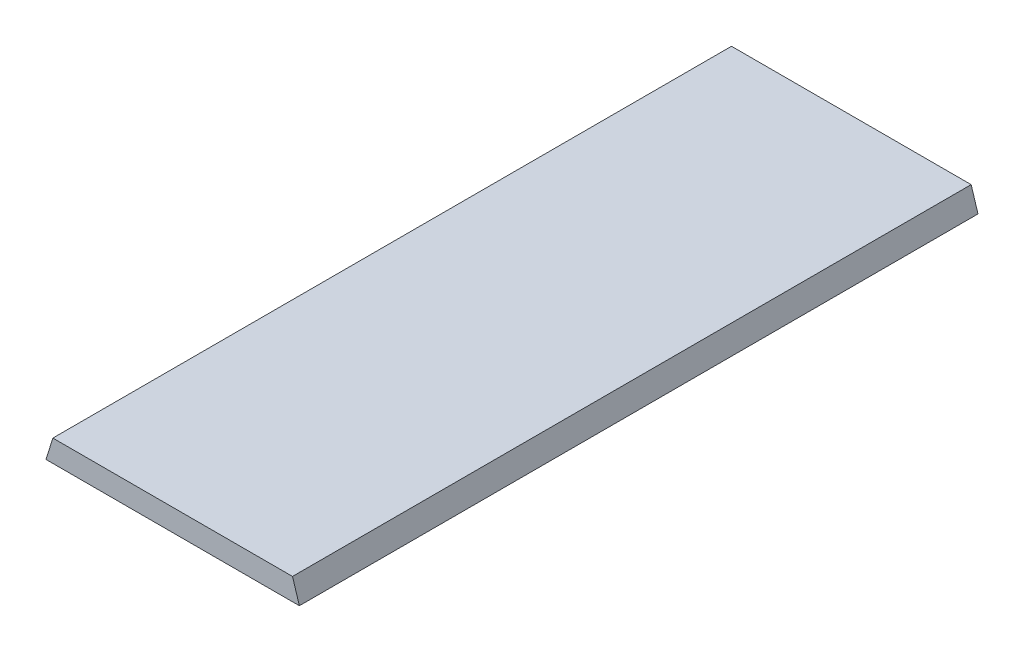
SolidWorks part; units mm, degrees
ref_plane "Front Plane" through (0, 0, 0) normal (0, 0, 1) x (1, 0, 0)
ref_plane "Top Plane" through (0, 0, 0) normal (0, 1, 0) x (1, 0, 0)
ref_plane "Right Plane" through (0, 0, 0) normal (1, 0, 0) x (0, 0, -1)
sketch "Sketch1" plane through (0, 0, 0) normal (0, 0, 1) x (1, 0, 0)
  line L0 (-9.8, 0) -> (9.8, 0)
  line L1 (-9.8, 0) -> (-9.2701, 1.7)
  line L2 (-9.2701, 1.7) -> (9.2701, 1.7)
  line L3 (9.2701, 1.7) -> (9.8, 0)
  line L4 (0, 0) -> (0, -58.1183) construction
  line L5 (0, -58.1183) -> (-30, -58.1183) construction
  line L6 (2, -43) -> (-2, -43)
  line L7 (0, -42.8683) -> (0, -58.1183) construction
  line L8 (-15, -10) -> (-30, -58.1183) construction
  line L9 (-9.2701, 1.7) -> (0, 31.4373) construction
  line L10 (0, 31.4373) -> (9.2701, 1.7) construction
  circle A0 centre (0, -58.1183) radius 15.25 construction
  point P4 (0, 0)
  point P11 (-14.8, -12.3169)
  point P19 (0, -43)
  dimension "D5" = 30.5
  dimension "D1" = 19.6
  dimension "D2" = 1.7
  dimension "D3" = 4
  dimension "D4" = 33
  dimension "D6" = 30
  dimension "D7" = 15
  dimension "D8" = 10
extrude "Boss-Extrude1" add sketch "Sketch1" against normal blind 52.5 contours L2 L3 L0 L1
